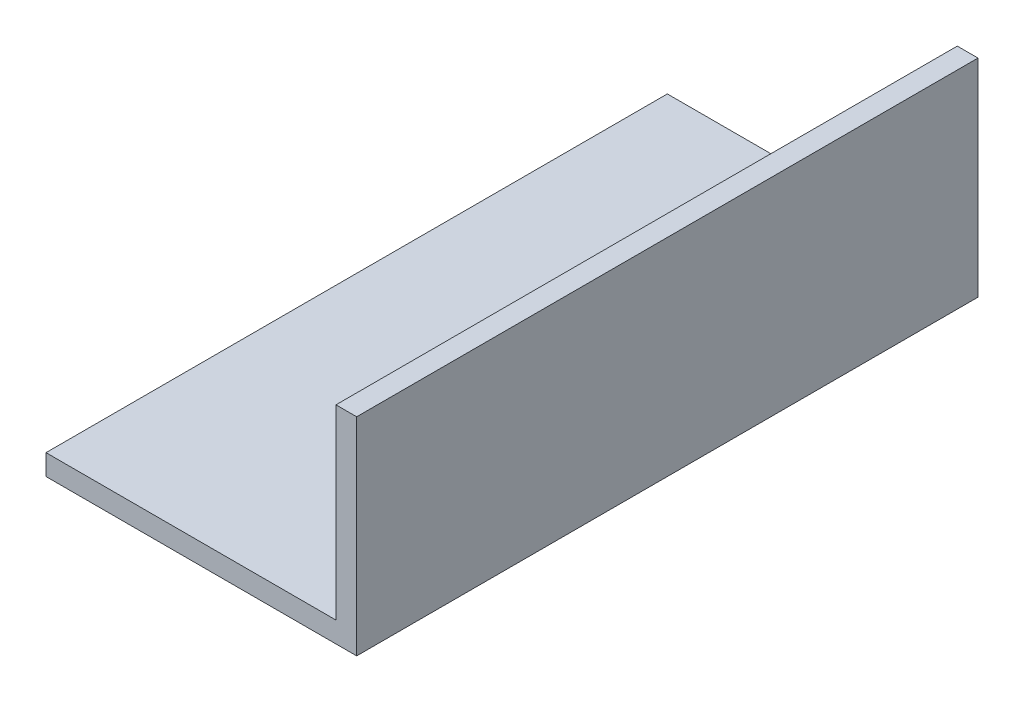
SolidWorks part; units mm, degrees
ref_plane "Front" through (0, 0, 0) normal (0, 0, 1) x (1, 0, 0)
ref_plane "Top" through (0, 0, 0) normal (0, 1, 0) x (1, 0, 0)
ref_plane "Right" through (0, 0, 0) normal (1, 0, 0) x (0, 0, -1)
sketch "Sketch1" plane through (0, 0, 0) normal (0, 0, 1) x (1, 0, 0)
  line L0 (16.51, 12.7) -> (16.51, -10.16)
  line L1 (16.51, -10.16) -> (-19.05, -10.16)
  line L2 (-19.05, -10.16) -> (-19.05, -12.7)
  line L3 (-19.05, -12.7) -> (19.05, -12.7)
  line L4 (19.05, -12.7) -> (19.05, 12.7)
  line L5 (19.05, 12.7) -> (16.51, 12.7)
  line L6 (-19.05, -12.7) -> (19.05, 12.7) construction
  dimension "D1" = 25.4
  dimension "D2" = 38.1
  dimension "D3" = 2.54
extrude "Boss-Extrude2" add sketch "Sketch1" along normal mid plane 76.2
